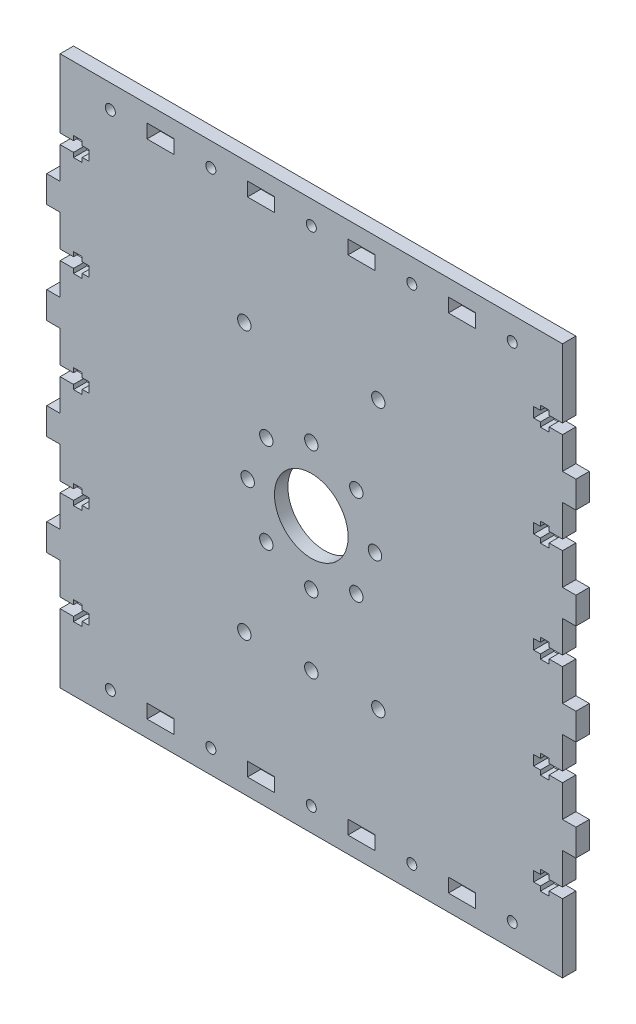
SolidWorks part; units mm, degrees
ref_plane "前视基准面" through (0, 0, 0) normal (0, 0, 1) x (1, 0, 0)
ref_plane "上视基准面" through (0, 0, 0) normal (0, 1, 0) x (1, 0, 0)
ref_plane "右视基准面" through (0, 0, 0) normal (1, 0, 0) x (0, 0, -1)
sketch "草图1" plane through (0, 0, 0) normal (0, 0, 1) x (1, 0, 0)
  line L9 (145, 46.5) -> (149, 46.5)
  line L10 (149, 46.5) -> (149, 45.15)
  line L11 (149, 45.15) -> (151.6, 45.15)
  line L12 (151.6, 45.15) -> (151.6, 46.5)
  line L13 (151.6, 46.5) -> (153.6, 46.5)
  line L14 (153.6, 46.5) -> (153.6, 49.5)
  line L23 (145, 48) -> (143.6922, 48) construction
  line L24 (145, 46.5) -> (145, 49.5) construction
  line L25 (151.6, 50.85) -> (151.6, 49.5)
  line L26 (149, 49.5) -> (149, 50.85)
  line L27 (151.6, 49.5) -> (153.6, 49.5)
  line L28 (149, 50.85) -> (151.6, 50.85)
  line L29 (145, 49.5) -> (149, 49.5)
  line L31 (145, 29) -> (141, 29)
  line L32 (141, 29) -> (141, 37)
  line L33 (141, 37) -> (145, 37)
  line L34 (145, 37) -> (145, 46.5)
  line L35 (141, 33) -> (142.703, 33) construction
  line L43 (149, 15.15) -> (151.6, 15.15)
  line L44 (151.6, 16.5) -> (153.6, 16.5)
  line L45 (149, 16.5) -> (149, 15.15)
  line L69 (286.4, 48) -> (153.6, 48) construction
  line L70 (151.6, 15.15) -> (151.6, 16.5)
  line L71 (153.6, 19.5) -> (153.6, 16.5)
  line L72 (151.6, 19.5) -> (153.6, 19.5)
  line L73 (151.6, 20.85) -> (151.6, 19.5)
  line L98 (149, 20.85) -> (151.6, 20.85)
  line L123 (149, 19.5) -> (149, 20.85)
  line L124 (145, 7) -> (145, 16.5)
  line L125 (149, 16.5) -> (145, 16.5)
  line L126 (149, 19.5) -> (145, 19.5)
  line L127 (145, 19.5) -> (145, 29)
  line L128 (153.6, 18) -> (150.6786, 18) construction
  line L129 (141, 3) -> (142.703, 3) construction
  line L130 (141, -1) -> (145, -1)
  line L131 (141, 7) -> (141, -1)
  line L132 (145, 7) -> (141, 7)
  line L133 (145, -1) -> (145, -10.5)
  line L134 (149, -10.5) -> (145, -10.5)
  line L135 (149, -13.5) -> (145, -13.5)
  line L136 (153.6, -12) -> (150.6786, -12) construction
  line L137 (149, -13.5) -> (149, -14.85)
  line L138 (149, -14.85) -> (151.6, -14.85)
  line L139 (151.6, -14.85) -> (151.6, -13.5)
  line L140 (151.6, -13.5) -> (153.6, -13.5)
  line L141 (153.6, -13.5) -> (153.6, -10.5)
  line L142 (151.6, -9.15) -> (151.6, -10.5)
  line L143 (149, -10.5) -> (149, -9.15)
  line L144 (151.6, -10.5) -> (153.6, -10.5)
  line L145 (149, -9.15) -> (151.6, -9.15)
  line L146 (153.6, 108) -> (150.6786, 108) construction
  line L147 (141, 93) -> (142.703, 93) construction
  line L148 (153.6, 78) -> (150.6786, 78) construction
  line L149 (141, 63) -> (142.703, 63) construction
  line L150 (145, 46.5) -> (149, 46.5)
  line L151 (149, 46.5) -> (149, 45.15)
  line L152 (149, 45.15) -> (151.6, 45.15)
  line L153 (151.6, 45.15) -> (151.6, 46.5)
  line L154 (151.6, 46.5) -> (153.6, 46.5)
  line L155 (151.6, 50.85) -> (151.6, 49.5)
  line L156 (149, 49.5) -> (149, 50.85)
  line L157 (151.6, 49.5) -> (153.6, 49.5)
  line L158 (145, 46.5) -> (149, 46.5)
  line L159 (149, 45.15) -> (151.6, 45.15)
  line L160 (151.6, 46.5) -> (153.6, 46.5)
  line L161 (149, 46.5) -> (149, 45.15)
  line L162 (151.6, 45.15) -> (151.6, 46.5)
  line L163 (151.6, 49.5) -> (153.6, 49.5)
  line L164 (151.6, 50.85) -> (151.6, 49.5)
  line L165 (149, 50.85) -> (151.6, 50.85)
  line L166 (149, 49.5) -> (149, 50.85)
  line L167 (145, 49.5) -> (149, 49.5)
  line L168 (149, 50.85) -> (151.6, 50.85)
  line L169 (145, 49.5) -> (149, 49.5)
  line L170 (149, 105.15) -> (151.6, 105.15)
  line L171 (151.6, 106.5) -> (153.6, 106.5)
  line L172 (149, 106.5) -> (149, 105.15)
  line L173 (151.6, 105.15) -> (151.6, 106.5)
  line L174 (153.6, 109.5) -> (153.6, 106.5)
  line L175 (151.6, 109.5) -> (153.6, 109.5)
  line L177 (151.6, 110.85) -> (151.6, 109.5)
  line L178 (149, 110.85) -> (151.6, 110.85)
  line L179 (149, 109.5) -> (149, 110.85)
  line L180 (149, 109.5) -> (145, 109.5)
  line L181 (149, 106.5) -> (145, 106.5)
  line L182 (145, 97) -> (145, 106.5)
  line L183 (145, 89) -> (141, 89)
  line L184 (141, 89) -> (141, 97)
  line L185 (141, 97) -> (145, 97)
  line L186 (145, 76.5) -> (145, 67)
  line L187 (149, 76.5) -> (145, 76.5)
  line L188 (149, 79.5) -> (145, 79.5)
  line L189 (145, 89) -> (145, 79.5)
  line L190 (149, 76.5) -> (149, 75.15)
  line L191 (149, 75.15) -> (151.6, 75.15)
  line L192 (151.6, 75.15) -> (151.6, 76.5)
  line L193 (151.6, 76.5) -> (153.6, 76.5)
  line L194 (153.6, 76.5) -> (153.6, 79.5)
  line L195 (151.6, 80.85) -> (151.6, 79.5)
  line L196 (149, 79.5) -> (149, 80.85)
  line L197 (151.6, 79.5) -> (153.6, 79.5)
  line L198 (149, 80.85) -> (151.6, 80.85)
  line L199 (145, 59) -> (145, 49.5)
  line L200 (141, 59) -> (145, 59)
  line L201 (141, 67) -> (141, 59)
  line L202 (145, 67) -> (141, 67)
  line L203 (145, 46.5) -> (149, 46.5)
  line L204 (149, 45.15) -> (151.6, 45.15)
  line L205 (151.6, 46.5) -> (153.6, 46.5)
  line L206 (149, 46.5) -> (149, 45.15)
  line L207 (151.6, 45.15) -> (151.6, 46.5)
  line L208 (151.6, 49.5) -> (153.6, 49.5)
  line L209 (151.6, 50.85) -> (151.6, 49.5)
  line L210 (149, 50.85) -> (151.6, 50.85)
  line L211 (149, 49.5) -> (149, 50.85)
  line L212 (145, 49.5) -> (149, 49.5)
  line L213 (220, 48) -> (220, 123) construction
  line L214 (145, 123) -> (145, 130)
  line L215 (295, 123) -> (295, 130)
  line L216 (145, 130) -> (295, 130)
  line L217 (209.06, -29.0645) -> (200.94, -24.9355) construction
  line L218 (209.06, -24.9355) -> (200.94, -29.0645) construction
  line L219 (205, -27) -> (205, -29.0645) construction
  line L220 (190, -27) -> (190, -36.5304) construction
  line L221 (205, -27) -> (175, -27) construction
  line L222 (175, -27) -> (175, -29.0645) construction
  line L223 (170.94, -24.9355) -> (179.06, -29.0645) construction
  line L224 (280, -27) -> (265, -27) construction
  line L225 (269.06, -29.0645) -> (260.94, -24.9355) construction
  line L227 (269.06, -24.9355) -> (260.94, -29.0645) construction
  line L228 (265, -27) -> (265, -29.0645) construction
  line L229 (235, -27) -> (265, -27) construction
  line L230 (250, -27) -> (250, -36.5304) construction
  line L231 (235, -27) -> (235, -29.0645) construction
  line L232 (230.94, -24.9355) -> (239.06, -29.0645) construction
  line L233 (230.94, -29.0645) -> (239.06, -24.9355) construction
  line L234 (170.94, -29.0645) -> (179.06, -24.9355) construction
  line L235 (160, -27) -> (175, -27) construction
  line L236 (209.06, -29.0645) -> (200.94, -29.0645)
  line L237 (209.06, -29.0645) -> (209.06, -24.9355)
  line L238 (209.06, -24.9355) -> (200.94, -24.9355)
  line L239 (200.94, -29.0645) -> (200.94, -24.9355)
  line L240 (179.06, -29.0645) -> (179.06, -24.9355)
  line L241 (170.94, -24.9355) -> (179.06, -24.9355)
  line L242 (170.94, -29.0645) -> (170.94, -24.9355)
  line L243 (170.94, -29.0645) -> (179.06, -29.0645)
  line L244 (269.06, -29.0645) -> (260.94, -29.0645)
  line L245 (269.06, -29.0645) -> (269.06, -24.9355)
  line L246 (269.06, -24.9355) -> (260.94, -24.9355)
  line L248 (260.94, -29.0645) -> (260.94, -24.9355)
  line L249 (239.06, -29.0645) -> (239.06, -24.9355)
  line L250 (230.94, -24.9355) -> (239.06, -24.9355)
  line L251 (230.94, -29.0645) -> (230.94, -24.9355)
  line L252 (230.94, -29.0645) -> (239.06, -29.0645)
  line L253 (145, -34) -> (295, -34)
  line L254 (295, -27) -> (295, -34)
  line L255 (145, -27) -> (145, -34)
  line L256 (220, 48) -> (220, 8) construction
  line L257 (220, 8) -> (200, 8) construction
  line L332 (295, 49.5) -> (291, 49.5)
  line L333 (291, 49.5) -> (291, 50.85)
  line L334 (291, 50.85) -> (288.4, 50.85)
  line L335 (288.4, 50.85) -> (288.4, 49.5)
  line L336 (288.4, 49.5) -> (286.4, 49.5)
  line L337 (286.4, 49.5) -> (286.4, 46.5)
  line L338 (288.4, 45.15) -> (288.4, 46.5)
  line L339 (291, 46.5) -> (291, 45.15)
  line L340 (288.4, 46.5) -> (286.4, 46.5)
  line L341 (291, 45.15) -> (288.4, 45.15)
  line L342 (295, 46.5) -> (291, 46.5)
  line L343 (295, 67) -> (299, 67)
  line L344 (299, 67) -> (299, 59)
  line L345 (299, 59) -> (295, 59)
  line L346 (295, 59) -> (295, 49.5)
  line L347 (291, 80.85) -> (288.4, 80.85)
  line L348 (288.4, 79.5) -> (286.4, 79.5)
  line L349 (291, 79.5) -> (291, 80.85)
  line L350 (288.4, 80.85) -> (288.4, 79.5)
  line L351 (286.4, 76.5) -> (286.4, 79.5)
  line L352 (288.4, 76.5) -> (286.4, 76.5)
  line L353 (288.4, 75.15) -> (288.4, 76.5)
  line L354 (291, 75.15) -> (288.4, 75.15)
  line L355 (291, 76.5) -> (291, 75.15)
  line L356 (295, 89) -> (295, 79.5)
  line L357 (291, 79.5) -> (295, 79.5)
  line L358 (291, 76.5) -> (295, 76.5)
  line L359 (295, 76.5) -> (295, 67)
  line L360 (299, 97) -> (295, 97)
  line L361 (299, 89) -> (299, 97)
  line L362 (295, 89) -> (299, 89)
  line L363 (295, 97) -> (295, 106.5)
  line L364 (291, 106.5) -> (295, 106.5)
  line L365 (291, 109.5) -> (295, 109.5)
  line L366 (291, 109.5) -> (291, 110.85)
  line L367 (291, 110.85) -> (288.4, 110.85)
  line L369 (288.4, 110.85) -> (288.4, 109.5)
  line L370 (288.4, 109.5) -> (286.4, 109.5)
  line L371 (286.4, 109.5) -> (286.4, 106.5)
  line L372 (288.4, 105.15) -> (288.4, 106.5)
  line L373 (291, 106.5) -> (291, 105.15)
  line L374 (288.4, 106.5) -> (286.4, 106.5)
  line L375 (291, 105.15) -> (288.4, 105.15)
  line L376 (295, 49.5) -> (291, 49.5)
  line L377 (291, 49.5) -> (291, 50.85)
  line L378 (291, 50.85) -> (288.4, 50.85)
  line L379 (288.4, 50.85) -> (288.4, 49.5)
  line L380 (288.4, 49.5) -> (286.4, 49.5)
  line L381 (160, 123) -> (175, 123) construction
  line L382 (170.94, 125.0645) -> (179.06, 120.9355) construction
  line L383 (230.94, 125.0645) -> (239.06, 125.0645)
  line L384 (230.94, 125.0645) -> (230.94, 120.9355)
  line L385 (288.4, 45.15) -> (288.4, 46.5)
  line L386 (291, 46.5) -> (291, 45.15)
  line L387 (288.4, 46.5) -> (286.4, 46.5)
  line L388 (295, 49.5) -> (291, 49.5)
  line L389 (291, 50.85) -> (288.4, 50.85)
  line L390 (288.4, 49.5) -> (286.4, 49.5)
  line L391 (291, 49.5) -> (291, 50.85)
  line L392 (288.4, 50.85) -> (288.4, 49.5)
  line L393 (288.4, 46.5) -> (286.4, 46.5)
  line L394 (288.4, 45.15) -> (288.4, 46.5)
  line L395 (291, 45.15) -> (288.4, 45.15)
  line L396 (291, 46.5) -> (291, 45.15)
  line L397 (295, 46.5) -> (291, 46.5)
  line L398 (291, 45.15) -> (288.4, 45.15)
  line L399 (295, 46.5) -> (291, 46.5)
  line L400 (291, -9.15) -> (288.4, -9.15)
  line L401 (288.4, -10.5) -> (286.4, -10.5)
  line L402 (291, -10.5) -> (291, -9.15)
  line L403 (288.4, -9.15) -> (288.4, -10.5)
  line L404 (286.4, -13.5) -> (286.4, -10.5)
  line L405 (288.4, -13.5) -> (286.4, -13.5)
  line L406 (288.4, -14.85) -> (288.4, -13.5)
  line L407 (291, -14.85) -> (288.4, -14.85)
  line L408 (291, -13.5) -> (291, -14.85)
  line L409 (291, -13.5) -> (295, -13.5)
  line L410 (291, -10.5) -> (295, -10.5)
  line L411 (295, -1) -> (295, -10.5)
  line L412 (295, 7) -> (299, 7)
  line L413 (299, 7) -> (299, -1)
  line L414 (299, -1) -> (295, -1)
  line L415 (295, 19.5) -> (295, 29)
  line L416 (291, 19.5) -> (295, 19.5)
  line L417 (230.94, 120.9355) -> (239.06, 120.9355)
  line L418 (239.06, 125.0645) -> (239.06, 120.9355)
  line L419 (230.94, 125.0645) -> (239.06, 120.9355) construction
  line L420 (230.94, 120.9355) -> (239.06, 125.0645) construction
  line L421 (235, 123) -> (235, 125.0645) construction
  line L422 (250, 123) -> (250, 132.5304) construction
  line L423 (235, 123) -> (265, 123) construction
  line L424 (265, 123) -> (265, 125.0645) construction
  line L425 (269.06, 120.9355) -> (260.94, 125.0645) construction
  line L426 (269.06, 125.0645) -> (260.94, 120.9355) construction
  line L427 (280, 123) -> (265, 123) construction
  line L428 (260.94, 125.0645) -> (260.94, 120.9355)
  line L429 (269.06, 120.9355) -> (260.94, 120.9355)
  line L430 (269.06, 125.0645) -> (269.06, 120.9355)
  line L431 (269.06, 125.0645) -> (260.94, 125.0645)
  line L432 (170.94, 120.9355) -> (179.06, 125.0645) construction
  line L433 (175, 123) -> (175, 125.0645) construction
  line L434 (291, 16.5) -> (295, 16.5)
  line L435 (205, 123) -> (175, 123) construction
  line L436 (190, 123) -> (190, 132.5304) construction
  line L437 (205, 123) -> (205, 125.0645) construction
  line L438 (295, 7) -> (295, 16.5)
  line L439 (291, 19.5) -> (291, 20.85)
  line L440 (291, 20.85) -> (288.4, 20.85)
  line L441 (288.4, 20.85) -> (288.4, 19.5)
  line L442 (288.4, 19.5) -> (286.4, 19.5)
  line L443 (286.4, 19.5) -> (286.4, 16.5)
  line L444 (288.4, 15.15) -> (288.4, 16.5)
  line L445 (291, 16.5) -> (291, 15.15)
  line L446 (288.4, 16.5) -> (286.4, 16.5)
  line L447 (291, 15.15) -> (288.4, 15.15)
  line L448 (295, 37) -> (295, 46.5)
  line L449 (299, 37) -> (295, 37)
  line L450 (299, 29) -> (299, 37)
  line L451 (295, 29) -> (299, 29)
  line L452 (209.06, 120.9355) -> (200.94, 125.0645) construction
  line L453 (295, 49.5) -> (291, 49.5)
  line L454 (291, 50.85) -> (288.4, 50.85)
  line L455 (288.4, 49.5) -> (286.4, 49.5)
  line L456 (291, 49.5) -> (291, 50.85)
  line L457 (288.4, 50.85) -> (288.4, 49.5)
  line L458 (209.06, 125.0645) -> (200.94, 120.9355) construction
  line L459 (170.94, 125.0645) -> (179.06, 125.0645)
  line L460 (170.94, 125.0645) -> (170.94, 120.9355)
  line L461 (288.4, 46.5) -> (286.4, 46.5)
  line L462 (288.4, 45.15) -> (288.4, 46.5)
  line L463 (291, 45.15) -> (288.4, 45.15)
  line L464 (291, 46.5) -> (291, 45.15)
  line L465 (295, 46.5) -> (291, 46.5)
  line L466 (295, 48) -> (296.3078, 48) construction
  line L467 (295, 49.5) -> (295, 46.5) construction
  line L468 (299, 63) -> (297.297, 63) construction
  line L469 (286.4, 78) -> (289.3214, 78) construction
  line L470 (299, 93) -> (297.297, 93) construction
  line L471 (286.4, 108) -> (289.3214, 108) construction
  line L472 (286.4, -12) -> (289.3214, -12) construction
  line L473 (299, 3) -> (297.297, 3) construction
  line L474 (286.4, 18) -> (289.3214, 18) construction
  line L475 (299, 33) -> (297.297, 33) construction
  line L592 (145, 123) -> (145, 109.5)
  line L594 (145, -27) -> (145, -13.5)
  line L595 (295, -13.5) -> (295, -27)
  line L598 (295, 123) -> (295, 109.5)
  line L599 (170.94, 120.9355) -> (179.06, 120.9355)
  line L600 (179.06, 125.0645) -> (179.06, 120.9355)
  line L601 (200.94, 125.0645) -> (200.94, 120.9355)
  line L602 (209.06, 120.9355) -> (200.94, 120.9355)
  line L603 (209.06, 125.0645) -> (209.06, 120.9355)
  line L604 (209.06, 125.0645) -> (200.94, 125.0645)
  line L606 (218.5, 123) -> (218.5, 119) [skipped]
  line L607 (218.5, 119) -> (217.15, 119) [skipped]
  line L608 (217.15, 119) -> (217.15, 116.4) [skipped]
  line L609 (217.15, 116.4) -> (218.5, 116.4) [skipped]
  line L610 (221.5, 119) -> (222.85, 119) [skipped]
  line L611 (221.5, 123) -> (221.5, 119) [skipped]
  line L612 (201, 123) -> (201, 127) [skipped]
  line L613 (201, 127) -> (209, 127) [skipped]
  line L614 (209, 127) -> (209, 123) [skipped]
  line L615 (209, 123) -> (218.5, 123) [skipped]
  line L616 (187.15, 119) -> (187.15, 116.4) [skipped]
  line L617 (188.5, 119) -> (187.15, 119) [skipped]
  line L618 (187.15, 116.4) -> (188.5, 116.4) [skipped]
  line L619 (192.85, 116.4) -> (191.5, 116.4) [skipped]
  line L620 (192.85, 119) -> (192.85, 116.4) [skipped]
  line L621 (191.5, 119) -> (192.85, 119) [skipped]
  line L622 (179, 123) -> (188.5, 123) [skipped]
  line L623 (188.5, 119) -> (188.5, 123) [skipped]
  line L624 (191.5, 119) -> (191.5, 123) [skipped]
  line L625 (191.5, 123) -> (201, 123) [skipped]
  line L626 (171, 127) -> (171, 123) [skipped]
  line L627 (179, 127) -> (171, 127) [skipped]
  line L628 (179, 123) -> (179, 127) [skipped]
  line L629 (171, 123) -> (161.5, 123) [skipped]
  line L630 (161.5, 119) -> (161.5, 123) [skipped]
  line L631 (158.5, 119) -> (158.5, 123) [skipped]
  line L632 (158.5, 119) -> (157.15, 119) [skipped]
  line L633 (157.15, 119) -> (157.15, 116.4) [skipped]
  line L634 (157.15, 116.4) -> (158.5, 116.4) [skipped]
  line L635 (158.5, 116.4) -> (158.5, 114.4) [skipped]
  line L636 (158.5, 114.4) -> (161.5, 114.4) [skipped]
  line L637 (162.85, 116.4) -> (161.5, 116.4) [skipped]
  line L638 (161.5, 119) -> (162.85, 119) [skipped]
  line L639 (161.5, 116.4) -> (161.5, 114.4) [skipped]
  line L640 (162.85, 119) -> (162.85, 116.4) [skipped]
  line L641 (218.5, 123) -> (218.5, 119) [skipped]
  line L642 (218.5, 119) -> (217.15, 119) [skipped]
  line L643 (217.15, 119) -> (217.15, 116.4) [skipped]
  line L644 (217.15, 116.4) -> (218.5, 116.4) [skipped]
  line L645 (221.5, 119) -> (222.85, 119) [skipped]
  line L646 (218.5, 123) -> (218.5, 119) [skipped]
  line L647 (217.15, 119) -> (217.15, 116.4) [skipped]
  line L648 (218.5, 119) -> (217.15, 119) [skipped]
  line L649 (217.15, 116.4) -> (218.5, 116.4) [skipped]
  line L650 (221.5, 119) -> (222.85, 119) [skipped]
  line L651 (221.5, 123) -> (221.5, 119) [skipped]
  line L652 (221.5, 123) -> (221.5, 119) [skipped]
  line L653 (269, 123) -> (278.5, 123) [skipped]
  line L654 (261, 123) -> (261, 127) [skipped]
  line L655 (261, 127) -> (269, 127) [skipped]
  line L656 (269, 127) -> (269, 123) [skipped]
  line L657 (248.5, 123) -> (239, 123) [skipped]
  line L658 (248.5, 119) -> (248.5, 123) [skipped]
  line L659 (251.5, 119) -> (251.5, 123) [skipped]
  line L660 (261, 123) -> (251.5, 123) [skipped]
  line L661 (248.5, 119) -> (247.15, 119) [skipped]
  line L662 (251.5, 119) -> (252.85, 119) [skipped]
  line L663 (231, 123) -> (221.5, 123) [skipped]
  line L664 (231, 127) -> (231, 123) [skipped]
  line L665 (239, 127) -> (231, 127) [skipped]
  line L666 (239, 123) -> (239, 127) [skipped]
  line L667 (218.5, 123) -> (218.5, 119) [skipped]
  line L668 (217.15, 119) -> (217.15, 116.4) [skipped]
  line L669 (218.5, 119) -> (217.15, 119) [skipped]
  line L670 (217.15, 116.4) -> (218.5, 116.4) [skipped]
  line L671 (221.5, 119) -> (222.85, 119) [skipped]
  line L672 (221.5, 123) -> (221.5, 119) [skipped]
  line L673 (220, 123) -> (220, 124.3078) construction
  line L674 (218.5, 123) -> (221.5, 123) construction
  line L675 (205, 127) -> (205, 125.297) construction
  line L676 (175, 127) -> (175, 125.297) construction
  line L677 (160, 114.4) -> (160, 117.3214) construction
  line L678 (265, 127) -> (265, 125.297) construction
  line L679 (235, 127) -> (235, 125.297) construction
  line L680 (218.5, 116.4) -> (218.5, 114.4) [skipped]
  line L681 (218.5, 114.4) -> (221.5, 114.4) [skipped]
  line L682 (222.85, 116.4) -> (221.5, 116.4) [skipped]
  line L683 (221.5, 116.4) -> (221.5, 114.4) [skipped]
  line L684 (222.85, 119) -> (222.85, 116.4) [skipped]
  line L685 (218.5, 116.4) -> (218.5, 114.4) [skipped]
  line L686 (222.85, 116.4) -> (221.5, 116.4) [skipped]
  line L687 (221.5, 116.4) -> (221.5, 114.4) [skipped]
  line L688 (218.5, 116.4) -> (218.5, 114.4) [skipped]
  line L689 (221.5, 116.4) -> (221.5, 114.4) [skipped]
  line L690 (222.85, 116.4) -> (221.5, 116.4) [skipped]
  line L691 (222.85, 119) -> (222.85, 116.4) [skipped]
  line L692 (222.85, 119) -> (222.85, 116.4) [skipped]
  line L693 (277.15, 119) -> (277.15, 116.4) [skipped]
  line L694 (278.5, 116.4) -> (278.5, 114.4) [skipped]
  line L695 (278.5, 119) -> (277.15, 119) [skipped]
  line L696 (277.15, 116.4) -> (278.5, 116.4) [skipped]
  line L697 (281.5, 114.4) -> (278.5, 114.4) [skipped]
  line L698 (281.5, 116.4) -> (281.5, 114.4) [skipped]
  line L699 (282.85, 116.4) -> (281.5, 116.4) [skipped]
  line L700 (282.85, 119) -> (282.85, 116.4) [skipped]
  line L701 (281.5, 119) -> (282.85, 119) [skipped]
  line L702 (281.5, 119) -> (281.5, 123) [skipped]
  line L703 (278.5, 119) -> (278.5, 123) [skipped]
  line L704 (247.15, 119) -> (247.15, 116.4) [skipped]
  line L705 (247.15, 116.4) -> (248.5, 116.4) [skipped]
  line L706 (248.5, 116.4) -> (248.5, 114.4) [skipped]
  line L707 (248.5, 114.4) -> (251.5, 114.4) [skipped]
  line L708 (252.85, 116.4) -> (251.5, 116.4) [skipped]
  line L709 (251.5, 116.4) -> (251.5, 114.4) [skipped]
  line L710 (252.85, 119) -> (252.85, 116.4) [skipped]
  line L711 (218.5, 116.4) -> (218.5, 114.4) [skipped]
  line L712 (221.5, 116.4) -> (221.5, 114.4) [skipped]
  line L713 (222.85, 116.4) -> (221.5, 116.4) [skipped]
  line L714 (222.85, 119) -> (222.85, 116.4) [skipped]
  line L715 (280, 114.4) -> (280, 117.3214) construction
  line L716 (250, 114.4) -> (250, 117.3214) construction
  line L717 (188.5, 116.4) -> (188.5, 114.4) [skipped]
  line L718 (191.5, 114.4) -> (188.5, 114.4) [skipped]
  line L719 (191.5, 116.4) -> (191.5, 114.4) [skipped]
  line L720 (190, 114.4) -> (190, 117.3214) construction
  line L721 (221.5, -27) -> (221.5, -23) [skipped]
  line L722 (221.5, -23) -> (222.85, -23) [skipped]
  line L723 (222.85, -23) -> (222.85, -20.4) [skipped]
  line L724 (222.85, -20.4) -> (221.5, -20.4) [skipped]
  line L725 (221.5, -20.4) -> (221.5, -18.4) [skipped]
  line L726 (221.5, -18.4) -> (218.5, -18.4) [skipped]
  line L727 (217.15, -20.4) -> (218.5, -20.4) [skipped]
  line L728 (218.5, -23) -> (217.15, -23) [skipped]
  line L729 (218.5, -20.4) -> (218.5, -18.4) [skipped]
  line L730 (217.15, -23) -> (217.15, -20.4) [skipped]
  line L731 (218.5, -27) -> (218.5, -23) [skipped]
  line L732 (239, -27) -> (239, -31) [skipped]
  line L733 (239, -31) -> (231, -31) [skipped]
  line L734 (231, -31) -> (231, -27) [skipped]
  line L735 (231, -27) -> (221.5, -27) [skipped]
  line L736 (252.85, -23) -> (252.85, -20.4) [skipped]
  line L737 (251.5, -20.4) -> (251.5, -18.4) [skipped]
  line L738 (251.5, -23) -> (252.85, -23) [skipped]
  line L739 (252.85, -20.4) -> (251.5, -20.4) [skipped]
  line L740 (248.5, -18.4) -> (251.5, -18.4) [skipped]
  line L741 (248.5, -20.4) -> (248.5, -18.4) [skipped]
  line L742 (247.15, -20.4) -> (248.5, -20.4) [skipped]
  line L743 (247.15, -23) -> (247.15, -20.4) [skipped]
  line L744 (248.5, -23) -> (247.15, -23) [skipped]
  line L745 (261, -27) -> (251.5, -27) [skipped]
  line L746 (251.5, -23) -> (251.5, -27) [skipped]
  line L747 (248.5, -23) -> (248.5, -27) [skipped]
  line L748 (248.5, -27) -> (239, -27) [skipped]
  line L749 (269, -31) -> (269, -27) [skipped]
  line L750 (261, -31) -> (269, -31) [skipped]
  line L751 (261, -27) -> (261, -31) [skipped]
  line L752 (269, -27) -> (278.5, -27) [skipped]
  line L753 (278.5, -23) -> (278.5, -27) [skipped]
  line L754 (281.5, -23) -> (281.5, -27) [skipped]
  line L755 (281.5, -23) -> (282.85, -23) [skipped]
  line L756 (282.85, -23) -> (282.85, -20.4) [skipped]
  line L757 (282.85, -20.4) -> (281.5, -20.4) [skipped]
  line L758 (281.5, -20.4) -> (281.5, -18.4) [skipped]
  line L759 (281.5, -18.4) -> (278.5, -18.4) [skipped]
  line L760 (277.15, -20.4) -> (278.5, -20.4) [skipped]
  line L761 (278.5, -23) -> (277.15, -23) [skipped]
  line L762 (278.5, -20.4) -> (278.5, -18.4) [skipped]
  line L763 (277.15, -23) -> (277.15, -20.4) [skipped]
  line L764 (221.5, -27) -> (221.5, -23) [skipped]
  line L765 (221.5, -23) -> (222.85, -23) [skipped]
  line L766 (222.85, -23) -> (222.85, -20.4) [skipped]
  line L767 (222.85, -20.4) -> (221.5, -20.4) [skipped]
  line L768 (221.5, -20.4) -> (221.5, -18.4) [skipped]
  line L769 (217.15, -20.4) -> (218.5, -20.4) [skipped]
  line L770 (218.5, -23) -> (217.15, -23) [skipped]
  line L771 (218.5, -20.4) -> (218.5, -18.4) [skipped]
  line L772 (221.5, -27) -> (221.5, -23) [skipped]
  line L773 (222.85, -23) -> (222.85, -20.4) [skipped]
  line L774 (221.5, -20.4) -> (221.5, -18.4) [skipped]
  line L775 (221.5, -23) -> (222.85, -23) [skipped]
  line L776 (222.85, -20.4) -> (221.5, -20.4) [skipped]
  line L777 (218.5, -20.4) -> (218.5, -18.4) [skipped]
  line L778 (217.15, -20.4) -> (218.5, -20.4) [skipped]
  line L779 (217.15, -23) -> (217.15, -20.4) [skipped]
  line L780 (218.5, -23) -> (217.15, -23) [skipped]
  line L781 (218.5, -27) -> (218.5, -23) [skipped]
  line L782 (217.15, -23) -> (217.15, -20.4) [skipped]
  line L783 (218.5, -27) -> (218.5, -23) [skipped]
  line L784 (162.85, -23) -> (162.85, -20.4) [skipped]
  line L785 (161.5, -20.4) -> (161.5, -18.4) [skipped]
  line L786 (161.5, -23) -> (162.85, -23) [skipped]
  line L787 (162.85, -20.4) -> (161.5, -20.4) [skipped]
  line L788 (158.5, -18.4) -> (161.5, -18.4) [skipped]
  line L789 (158.5, -20.4) -> (158.5, -18.4) [skipped]
  line L790 (157.15, -20.4) -> (158.5, -20.4) [skipped]
  line L791 (157.15, -23) -> (157.15, -20.4) [skipped]
  line L792 (158.5, -23) -> (157.15, -23) [skipped]
  line L793 (158.5, -23) -> (158.5, -27) [skipped]
  line L794 (161.5, -23) -> (161.5, -27) [skipped]
  line L795 (171, -27) -> (161.5, -27) [skipped]
  line L796 (179, -27) -> (179, -31) [skipped]
  line L797 (179, -31) -> (171, -31) [skipped]
  line L798 (171, -31) -> (171, -27) [skipped]
  line L799 (191.5, -27) -> (201, -27) [skipped]
  line L800 (191.5, -23) -> (191.5, -27) [skipped]
  line L801 (188.5, -23) -> (188.5, -27) [skipped]
  line L802 (179, -27) -> (188.5, -27) [skipped]
  line L803 (191.5, -23) -> (192.85, -23) [skipped]
  line L804 (192.85, -23) -> (192.85, -20.4) [skipped]
  line L805 (192.85, -20.4) -> (191.5, -20.4) [skipped]
  line L806 (191.5, -20.4) -> (191.5, -18.4) [skipped]
  line L807 (191.5, -18.4) -> (188.5, -18.4) [skipped]
  line L808 (187.15, -20.4) -> (188.5, -20.4) [skipped]
  line L809 (188.5, -23) -> (187.15, -23) [skipped]
  line L810 (188.5, -20.4) -> (188.5, -18.4) [skipped]
  line L811 (187.15, -23) -> (187.15, -20.4) [skipped]
  line L812 (209, -27) -> (218.5, -27) [skipped]
  line L813 (209, -31) -> (209, -27) [skipped]
  line L814 (201, -31) -> (209, -31) [skipped]
  line L815 (201, -27) -> (201, -31) [skipped]
  line L816 (221.5, -27) -> (221.5, -23) [skipped]
  line L817 (222.85, -23) -> (222.85, -20.4) [skipped]
  line L818 (221.5, -20.4) -> (221.5, -18.4) [skipped]
  line L819 (221.5, -23) -> (222.85, -23) [skipped]
  line L820 (222.85, -20.4) -> (221.5, -20.4) [skipped]
  line L821 (218.5, -20.4) -> (218.5, -18.4) [skipped]
  line L822 (217.15, -20.4) -> (218.5, -20.4) [skipped]
  line L823 (217.15, -23) -> (217.15, -20.4) [skipped]
  line L824 (218.5, -23) -> (217.15, -23) [skipped]
  line L825 (218.5, -27) -> (218.5, -23) [skipped]
  line L826 (220, -27) -> (220, -28.3078) construction
  line L827 (221.5, -27) -> (218.5, -27) construction
  line L828 (235, -31) -> (235, -29.297) construction
  line L829 (250, -18.4) -> (250, -21.3214) construction
  line L830 (265, -31) -> (265, -29.297) construction
  line L831 (280, -18.4) -> (280, -21.3214) construction
  line L832 (160, -18.4) -> (160, -21.3214) construction
  line L833 (175, -31) -> (175, -29.297) construction
  line L834 (190, -18.4) -> (190, -21.3214) construction
  line L835 (205, -31) -> (205, -29.297) construction
  circle A6 centre (220, 48) radius 19 construction
  circle A7 centre (220, 29) radius 2
  circle A15 centre (220, 48) radius 11
  circle A51 centre (206.565, 34.565) radius 2
  circle A52 centre (201, 48) radius 2
  circle A53 centre (206.565, 61.435) radius 2
  circle A54 centre (220, 67) radius 2
  circle A55 centre (233.435, 61.435) radius 2
  circle A56 centre (239, 48) radius 2
  circle A57 centre (233.435, 34.565) radius 2
  circle A59 centre (220, 123) radius 1.5
  circle A60 centre (250, 123) radius 1.5
  circle A61 centre (280, 123) radius 1.5
  circle A62 centre (160, 123) radius 1.5
  circle A63 centre (190, 123) radius 1.5
  circle A64 centre (190, -27) radius 1.5
  circle A65 centre (160, -27) radius 1.5
  circle A66 centre (280, -27) radius 1.5
  circle A67 centre (250, -27) radius 1.5
  circle A68 centre (220, -27) radius 1.5
  circle A69 centre (200, 8) radius 2
  circle A70 centre (240, 8) radius 2
  circle A71 centre (240, 88) radius 2
  circle A72 centre (200, 88) radius 2
  circle A73 centre (220, 8) radius 2
  point P15 (144.3461, 48)
  dimension "D2" = 15
  dimension "D7" = 38
  dimension "D1" = 15
  dimension "D3" = 4
  dimension "D4" = 2
  dimension "D5" = 2.6
  dimension "D6" = 1.35
  dimension "D8" = 1.5
extrude "凸台-拉伸1" add sketch "草图1" along normal blind 4
sketch "草图3" plane through (145, 0, 0) normal (-1, 0, 0) x (0, 0, 1)
  line L0 (2, 16.5) -> (2, 19.5)
  line L1 (4, 16.5) -> (0, 16.5) construction
  line L2 (4, 19.5) -> (0, 19.5) construction
  circle A0 centre (2, 18) radius 1.5
